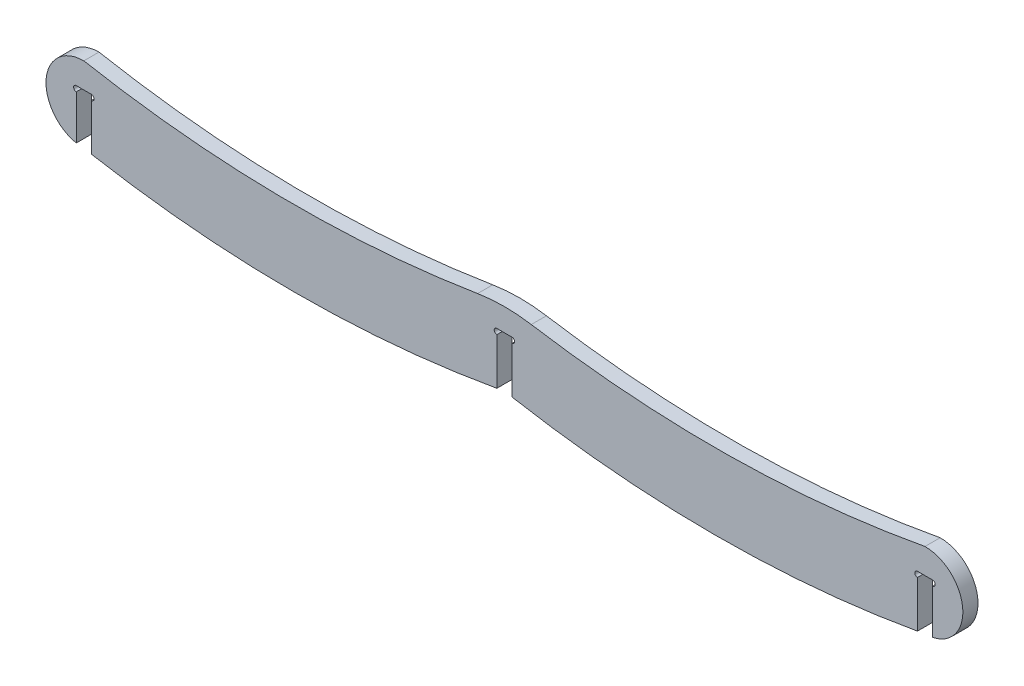
SolidWorks part; units mm, degrees
ref_plane "Piano frontale" through (0, 0, 0) normal (0, 0, 1) x (1, 0, 0)
ref_plane "Piano superiore" through (0, 0, 0) normal (0, 1, 0) x (1, 0, 0)
ref_plane "Piano destro" through (0, 0, 0) normal (1, 0, 0) x (0, 0, -1)
sketch "Schizzo1" plane through (0, 0, 0) normal (0, 0, 1) x (1, 0, 0)
  line L0 (-57.9889, 0) -> (942.0111, 0) construction
  line L1 (-66.9889, 56.825) -> (-48.9889, 56.825) construction
  line L2 (-66.9889, 60) -> (-48.9889, 60)
  line L3 (-66.9889, 53.65) -> (-48.9889, 53.65)
  line L4 (433.0111, 56.825) -> (451.0111, 56.825) construction
  line L5 (433.0111, 60) -> (451.0111, 60)
  line L6 (433.0111, 53.65) -> (451.0111, 53.65)
  line L7 (933.0111, 56.825) -> (951.0111, 56.825) construction
  line L8 (933.0111, 60) -> (951.0111, 60)
  line L9 (933.0111, 53.65) -> (951.0111, 53.65)
  line L10 (-57.9889, 90) -> (-57.9889, 60) construction
  line L12 (-66.9889, 53.65) -> (-48.9889, 53.65)
  line L13 (-66.9889, 53.65) -> (-66.9889, -107.9773)
  line L14 (-66.9889, -107.9773) -> (-48.9889, -107.9773)
  line L15 (-48.9889, 53.65) -> (-48.9889, -107.9773)
  line L16 (433.0111, 53.65) -> (451.0111, 53.65)
  line L17 (433.0111, 53.65) -> (433.0111, -107.9773)
  line L18 (433.0111, -107.9773) -> (451.0111, -107.9773)
  line L19 (451.0111, 53.65) -> (451.0111, -107.9773)
  line L20 (933.0111, 53.65) -> (951.0111, 53.65)
  line L21 (933.0111, 53.65) -> (933.0111, -107.9773)
  line L22 (933.0111, -107.9773) -> (951.0111, -107.9773)
  line L23 (951.0111, 53.65) -> (951.0111, -107.9773)
  arc A0 (-66.9889, 60) -> (-66.9889, 53.65) centre (-66.9889, 56.825) ccw
  arc A1 (-48.9889, 53.65) -> (-48.9889, 60) centre (-48.9889, 56.825) ccw
  circle A2 centre (-57.9889, 45) radius 45
  circle A3 centre (942.0111, 45) radius 45
  circle A4 centre (442.0111, 45) radius 45
  arc A5 (-57.9889, 90) -> (442.0111, 90) centre (192.0111, 1434.0907) ccw
  arc A6 (442.0111, 90) -> (942.0111, 90) centre (692.0111, 1434.0907) ccw
  arc A7 (442.0111, 0) -> (942.0111, 0) centre (692.0111, 1344.0907) ccw
  arc A8 (-57.9889, 0) -> (442.0111, 0) centre (192.0111, 1344.0907) ccw
  arc A9 (433.0111, 60) -> (433.0111, 53.65) centre (433.0111, 56.825) ccw
  arc A10 (451.0111, 53.65) -> (451.0111, 60) centre (451.0111, 56.825) ccw
  arc A11 (933.0111, 60) -> (933.0111, 53.65) centre (933.0111, 56.825) ccw
  arc A12 (951.0111, 53.65) -> (951.0111, 60) centre (951.0111, 56.825) ccw
  point P5 (-57.9889, 56.825)
  point P14 (442.0111, 56.825)
  point P34 (942.0111, 56.825)
  dimension "D1" = 6.35
  dimension "D2" = 18
  dimension "D3" = 1000
extrude "Estrusione-Estrusione1" add sketch "Schizzo1" along normal blind 18 contours A5 A2 L13 A0 L2 A1 L15 | L15 A8 L17 A4 A5 A2 | A10 L19 A4 A6 A5 L17 A9 L5 | L19 A7 L21 A3 A6 A4 | A12 L23 A3 A6 L21 A11 L8
fillet "Raccordo1" radius 200 1 edges at (442.0111, 90, 9)
